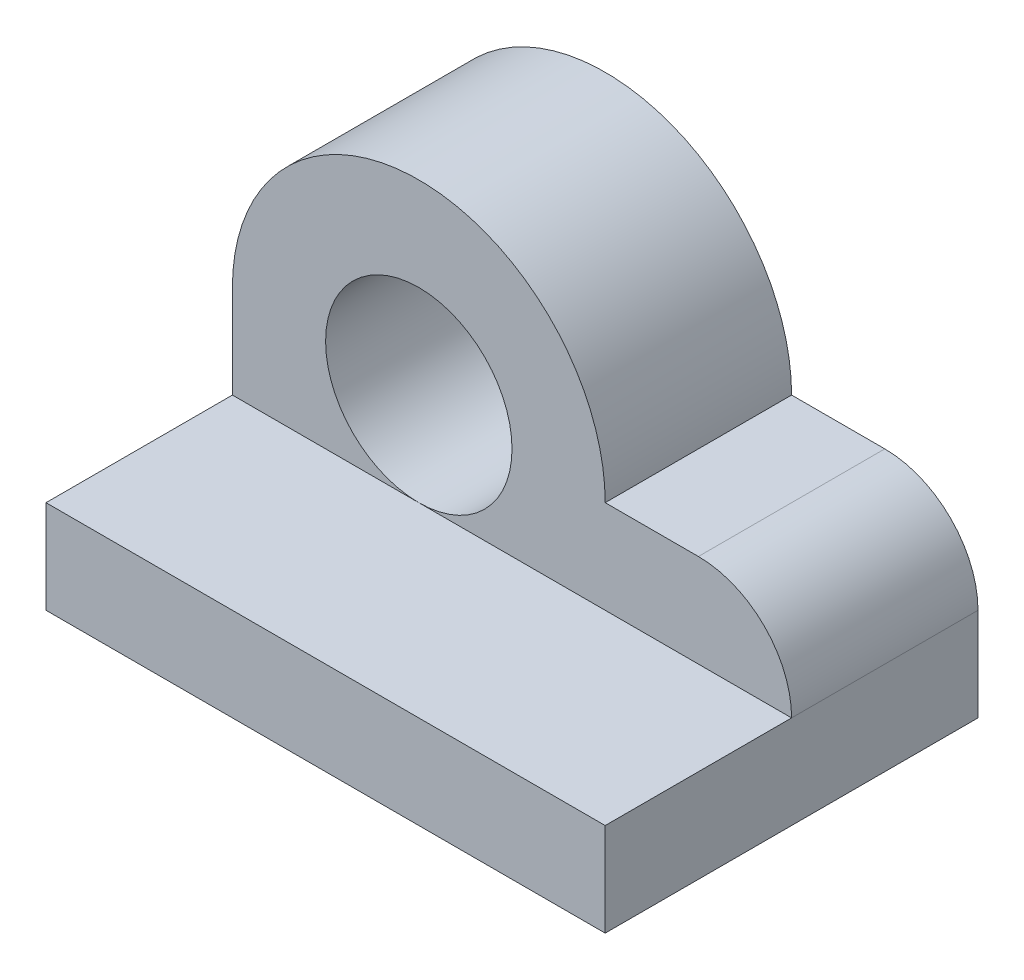
SolidWorks part; units mm, degrees
ref_plane "Front Plane" through (0, 0, 0) normal (0, 0, 1) x (1, 0, 0)
ref_plane "Top Plane" through (0, 0, 0) normal (0, 1, 0) x (1, 0, 0)
ref_plane "Right Plane" through (0, 0, 0) normal (1, 0, 0) x (0, 0, -1)
sketch "Sketch1" plane through (0, 0, 0) normal (0, 0, 1) x (1, 0, 0)
  line L0 (0, 0) -> (-60, 0)
  line L1 (-60, 0) -> (-60, 10)
  line L2 (-60, 10) -> (0, 10)
  line L3 (0, 10) -> (0, 0)
  point P7 (2.6966, -3.0337)
  dimension "D1" = 10
  dimension "D2" = 60
extrude "Boss-Extrude1" add sketch "Sketch1" against normal blind 40
ref_plane "Plane2" through (0, 0, -20) normal (0, 0, 1) x (1, 0, 0)
sketch "Sketch145" plane through (0, 0, -20) normal (0, 0, 1) x (1, 0, 0)
  line L0 (0, 10) -> (0, 20)
  line L1 (0, 20) -> (-20, 20)
  line L2 (-60, 10) -> (-60, 20)
  line L7 (0, 0) -> (0, 10)
  line L8 (0, 10) -> (-60, 10)
  line L9 (-60, 10) -> (-60, 0)
  line L10 (-60, 0) -> (0, 0)
  line L12 (0, 10) -> (-60, 10)
  arc A0 (-60, 20) -> (-20, 20) centre (-40, 20) cw
  dimension "D1" = 20
  dimension "D2" = 10
  dimension "D3" = 20
  dimension "D4" = 0
extrude "Boss-Extrude2" add sketch "Sketch145" against normal up to surface (20 mm away) up to face at (-30, 5, -40)
fillet "Fillet1" radius 10 1 edges at (0, 20, -30)
sketch "Sketch146" plane through (0, 0, -20) normal (0, 0, 1) x (1, 0, 0)
  circle A0 centre (-40, 20) radius 10
  dimension "D1" = 20
extrude "Cut-Extrude1" cut sketch "Sketch146" against normal through all
